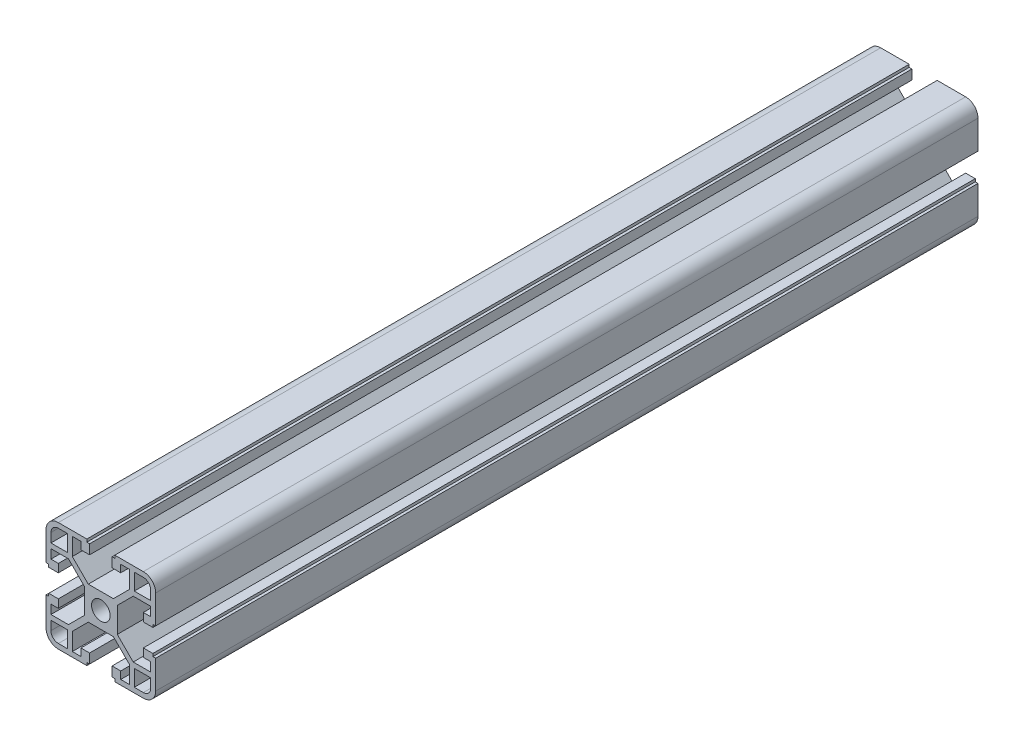
SolidWorks part; units mm, degrees
material "6063-T5"
ref_plane "Front Plane" through (0, 0, 0) normal (0, 0, 1) x (1, 0, 0)
ref_plane "Top Plane" through (0, 0, 0) normal (0, 1, 0) x (1, 0, 0)
ref_plane "Right Plane" through (0, 0, 0) normal (1, 0, 0) x (0, 0, -1)
sketch "Sketch3" plane through (0, 0, 0) normal (0, 0, 1) x (1, 0, 0)
  line L0 (17.9333, 92.7) -> (169.2667, 92.7) construction
  line L1 (-6, 6) -> (6, 6)
  line L2 (-6, 6) -> (-6, -6)
  line L3 (-6, -6) -> (6, -6)
  line L4 (6, 6) -> (6, -6)
  line L5 (0, 0) -> (20.1249, 20.1249) construction
  line L6 (4.5736, 4.5736) -> (11.4537, 11.4537) construction
  line L7 (5.2807, 3.8665) -> (12.0153, 10.6011)
  line L8 (3.8665, 5.2807) -> (10.7858, 12.2)
  line L13 (11.8142, 10.4) -> (18.2, 10.4)
  line L14 (6, 0) -> (23.1042, 0) construction
  line L15 (0, 6) -> (0, 13.9346) construction
  line L16 (4.5736, 4.5736) -> (11.8129, 11.8129) construction
  line L17 (5.2807, 3.8665) -> (12.52, 11.1058) construction
  line L18 (3.8665, 5.2807) -> (11.1058, 12.52) construction
  line L19 (10.4, 11.8142) -> (10.4, 18.2)
  line L20 (10.4, 18.2) -> (7.2581, 18.2)
  line L21 (-20, 20) -> (20, 20) construction
  line L22 (-20, 20) -> (-20, -20) construction
  line L23 (-20, -20) -> (20, -20) construction
  line L24 (20, 20) -> (20, -20) construction
  line L25 (7.2581, 18.2) -> (7.2581, 15.5)
  line L26 (7.2581, 15.5) -> (4.1, 15.5)
  line L27 (4.1, 15.5) -> (4.1, 19)
  line L28 (4.1, 19) -> (5.1, 19)
  line L29 (5.1, 19) -> (5.1, 20)
  line L30 (5.1, 20) -> (15.5, 20)
  line L31 (20, 15.5) -> (20, 5.1)
  line L32 (20, 5.1) -> (19, 5.1)
  line L33 (19, 5.1) -> (19, 4.1)
  line L34 (19, 4.1) -> (15.5, 4.1)
  line L35 (15.5, 4.1) -> (15.5, 7.1)
  line L36 (15.5, 7.1) -> (18.2, 7.1)
  line L37 (18.2, 7.1) -> (18.2, 10.4)
  line L42 (18.2, 12.2) -> (12.2, 12.2)
  line L43 (12.2, 18.2) -> (12.2, 18.2)
  line L44 (12.2, 18.2) -> (12.2, 18.2)
  line L45 (12.2, 18.2) -> (12.2, 18.2)
  line L46 (12.2, 18.2) -> (12.2, 18.2)
  line L47 (12.2, 18.2) -> (12.2, 18.2)
  line L48 (12.2, 18.2) -> (12.2, 18.2)
  line L49 (12.2, 18.2) -> (15.5, 18.2)
  line L50 (18.2, 15.5) -> (18.2, 12.2)
  line L51 (18.2, 12.2) -> (18.2, 12.2)
  line L52 (18.2, 12.2) -> (18.2, 12.2)
  line L53 (18.2, 12.2) -> (18.2, 12.2)
  line L54 (18.2, 12.2) -> (18.2, 12.2)
  line L55 (18.2, 12.2) -> (18.2, 12.2)
  line L56 (18.2, 12.2) -> (18.2, 12.2)
  line L57 (12.2, 12.2) -> (12.2, 18.2)
  line L58 (11.8142, 12.2) -> (18.2, 12.2) construction
  line L59 (12.2, 11.8142) -> (12.2, 18.2) construction
  line L60 (-18.2, 15.5) -> (-18.2, 12.2)
  line L61 (-12.2, 18.2) -> (-15.5, 18.2)
  line L62 (-12.2, 12.2) -> (-12.2, 18.2)
  line L63 (-18.2, 12.2) -> (-12.2, 12.2)
  line L64 (-11.8142, 10.4) -> (-18.2, 10.4)
  line L65 (-18.2, 7.1) -> (-18.2, 10.4)
  line L66 (-15.5, 7.1) -> (-18.2, 7.1)
  line L67 (-15.5, 4.1) -> (-15.5, 7.1)
  line L68 (-19, 4.1) -> (-15.5, 4.1)
  line L69 (-19, 5.1) -> (-19, 4.1)
  line L70 (-20, 5.1) -> (-19, 5.1)
  line L71 (-20, 15.5) -> (-20, 5.1)
  line L72 (-5.1, 20) -> (-15.5, 20)
  line L73 (-5.1, 19) -> (-5.1, 20)
  line L74 (-4.1, 19) -> (-5.1, 19)
  line L75 (-4.1, 15.5) -> (-4.1, 19)
  line L76 (-7.2581, 15.5) -> (-4.1, 15.5)
  line L77 (-7.2581, 18.2) -> (-7.2581, 15.5)
  line L78 (-10.4, 18.2) -> (-7.2581, 18.2)
  line L79 (-10.4, 11.8142) -> (-10.4, 18.2)
  line L80 (-10.4, 11.8142) -> (-4.5858, 6)
  line L81 (-11.8142, 10.4) -> (-6, 4.5858)
  line L82 (-18.2, -15.5) -> (-18.2, -12.2)
  line L83 (-18.2, -12.2) -> (-12.2, -12.2)
  line L84 (-12.2, -12.2) -> (-12.2, -18.2)
  line L85 (-12.2, -18.2) -> (-15.5, -18.2)
  line L86 (-20, -15.5) -> (-20, -5.1)
  line L87 (-20, -5.1) -> (-19, -5.1)
  line L88 (-19, -5.1) -> (-19, -4.1)
  line L89 (-19, -4.1) -> (-15.5, -4.1)
  line L90 (-15.5, -4.1) -> (-15.5, -7.1)
  line L91 (-15.5, -7.1) -> (-18.2, -7.1)
  line L92 (-18.2, -7.1) -> (-18.2, -10.4)
  line L93 (-11.8142, -10.4) -> (-18.2, -10.4)
  line L94 (-11.8142, -10.4) -> (-6, -4.5858)
  line L95 (-10.4, -11.8142) -> (-4.5858, -6)
  line L96 (-10.4, -11.8142) -> (-10.4, -18.2)
  line L97 (-10.4, -18.2) -> (-7.2581, -18.2)
  line L98 (-7.2581, -18.2) -> (-7.2581, -15.5)
  line L99 (-7.2581, -15.5) -> (-4.1, -15.5)
  line L100 (-4.1, -15.5) -> (-4.1, -19)
  line L101 (-4.1, -19) -> (-5.1, -19)
  line L102 (-5.1, -19) -> (-5.1, -20)
  line L103 (-5.1, -20) -> (-15.5, -20)
  line L104 (12.2, -18.2) -> (15.5, -18.2)
  line L105 (12.2, -12.2) -> (12.2, -18.2)
  line L106 (18.2, -12.2) -> (12.2, -12.2)
  line L107 (18.2, -15.5) -> (18.2, -12.2)
  line L108 (5.1, -20) -> (15.5, -20)
  line L109 (5.1, -19) -> (5.1, -20)
  line L110 (4.1, -19) -> (5.1, -19)
  line L111 (4.1, -15.5) -> (4.1, -19)
  line L112 (7.2581, -15.5) -> (4.1, -15.5)
  line L113 (10.4, -18.2) -> (7.2581, -18.2)
  line L114 (7.2581, -18.2) -> (7.2581, -15.5)
  line L115 (10.4, -11.8142) -> (10.4, -18.2)
  line L116 (10.4, -11.8142) -> (4.5858, -6)
  line L117 (11.8142, -10.4) -> (6, -4.5858)
  line L118 (11.8142, -10.4) -> (18.2, -10.4)
  line L119 (18.2, -7.1) -> (18.2, -10.4)
  line L120 (20, -15.5) -> (20, -5.1)
  line L121 (20, -5.1) -> (19, -5.1)
  line L122 (19, -5.1) -> (19, -4.1)
  line L123 (15.5, -7.1) -> (18.2, -7.1)
  line L124 (15.5, -4.1) -> (15.5, -7.1)
  line L125 (19, -4.1) -> (15.5, -4.1)
  circle A0 centre (0, 0) radius 3.4
  arc A1 (15.5, 20) -> (20, 15.5) centre (15.5, 15.5) cw
  arc A2 (15.5, 18.2) -> (18.2, 15.5) centre (15.5, 15.5) cw
  arc A3 (-15.5, 18.2) -> (-18.2, 15.5) centre (-15.5, 15.5) ccw
  arc A4 (-15.5, 20) -> (-20, 15.5) centre (-15.5, 15.5) ccw
  arc A5 (-15.5, -18.2) -> (-18.2, -15.5) centre (-15.5, -15.5) cw
  arc A6 (-15.5, -20) -> (-20, -15.5) centre (-15.5, -15.5) cw
  arc A7 (15.5, -18.2) -> (18.2, -15.5) centre (15.5, -15.5) ccw
  arc A8 (15.5, -20) -> (20, -15.5) centre (15.5, -15.5) ccw
  point P7 (6, 0)
  point P8 (0, 6)
  point P36 (0, 20)
  point P37 (-20, 0)
  dimension "D3" = 6.8
  dimension "D28" = 4.5
  dimension "D1" = 12
  dimension "D2" = 12
  dimension "D6" = 10.4
  dimension "D7" = 10.4
  dimension "D8" = 40
  dimension "D9" = 40
  dimension "D10" = 1
  dimension "D11" = 1
  dimension "D12" = 1.8
  dimension "D13" = 1.8
  dimension "D14" = 2
  dimension "D17" = 1.8
  dimension "D18" = 1.8
  dimension "D19" = 1
  dimension "D20" = 1
  dimension "D21" = 3.5
  dimension "D22" = 5.1
  dimension "D23" = 4.1
  dimension "D24" = 3
  dimension "D25" = 3.5
  dimension "D26" = 4.1
  dimension "D27" = 5.1
  dimension "D4" = 1
  dimension "D5" = 1
  dimension "D29" = 1.8
extrude "Boss-Extrude1" add sketch "Sketch3" along normal blind 300
